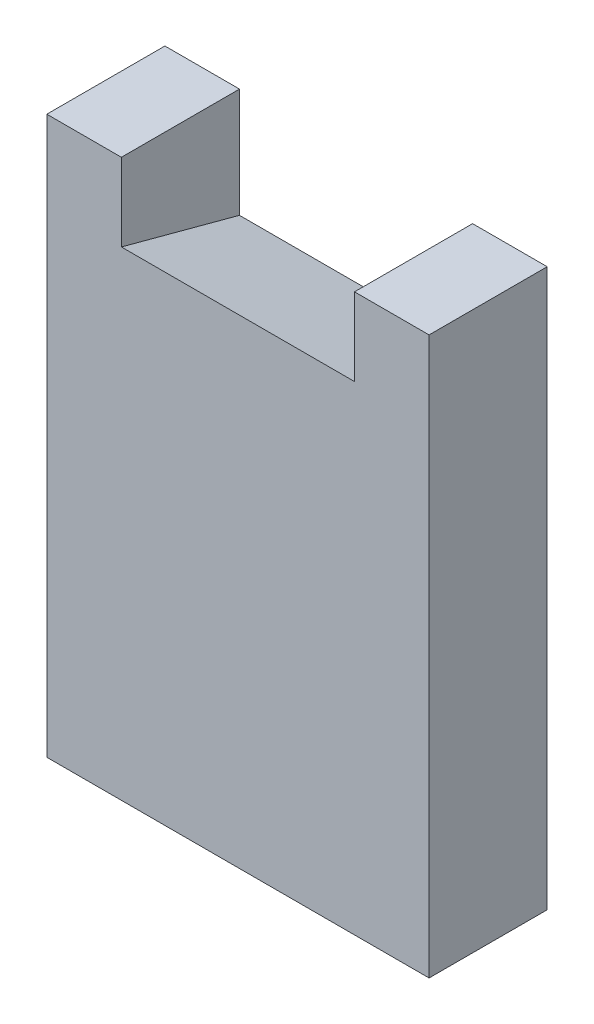
SolidWorks part; units mm, degrees
ref_plane "前视基准面" through (0, 0, 0) normal (0, 0, 1) x (1, 0, 0)
ref_plane "上视基准面" through (0, 0, 0) normal (0, 1, 0) x (1, 0, 0)
ref_plane "右视基准面" through (0, 0, 0) normal (1, 0, 0) x (0, 0, -1)
sketch "草图1" plane through (0, 0, 0) normal (0, 0, 1) x (1, 0, 0)
  line L1 (0, 0) -> (24.6, 0)
  line L2 (0, 0) -> (0, -35.84)
  line L3 (0, -35.84) -> (24.6, -35.84)
  line L4 (24.6, 0) -> (24.6, -35.84)
  line L5 (4.8, 0) -> (19.8, 0)
  line L6 (4.8, 0) -> (4.8, -5)
  line L7 (4.8, -5) -> (19.8, -5)
  line L8 (19.8, 0) -> (19.8, -5)
  point P9 (12.3, 0)
  dimension "D1" = 5
  dimension "D2" = 24.6
  dimension "D3" = 15
  dimension "D4" = 30.84
extrude "凸台-拉伸1" add sketch "草图1" along normal blind 7.6 contours L1 L8 L7 L6 L2 L3 L4
draft "拔模5" type of draft neutral plane draft angle 15 faces to draft 1 face at (12.3, -5, 3.8) neutral plane through (0, 0, 7.6) neutral plane normal (0, 0, 1) reverse direction yes parameters "D1"=15
